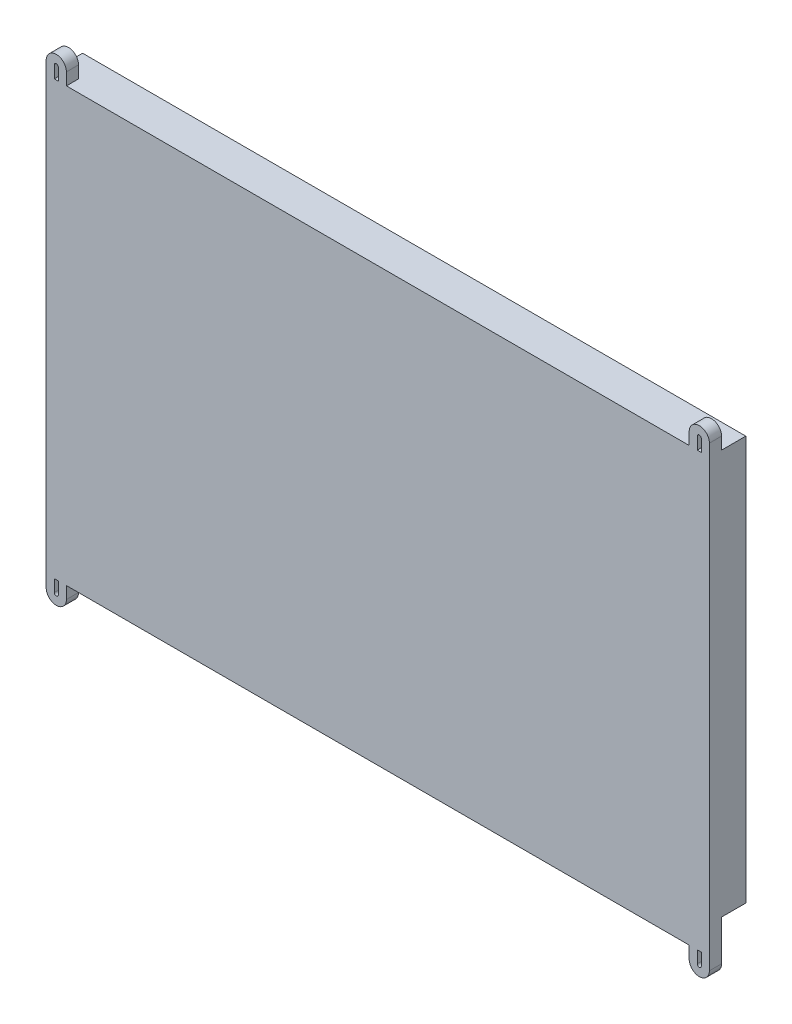
SolidWorks part; units mm, degrees
ref_plane "Plano frontal" through (0, 0, 0) normal (0, 0, 1) x (1, 0, 0)
ref_plane "Plano superior" through (0, 0, 0) normal (0, 1, 0) x (1, 0, 0)
ref_plane "Plano direito" through (0, 0, 0) normal (1, 0, 0) x (0, 0, -1)
sketch "Esboço1" plane through (0, 0, 0) normal (0, 0, 1) x (1, 0, 0)
  line L1 (-89.6416, -52.0983) -> (74.3584, -52.0983)
  line L2 (-89.6416, -52.0983) -> (-89.6416, 54.9017)
  line L3 (-89.6416, 54.9017) -> (74.3584, 54.9017)
  line L4 (74.3584, -52.0983) -> (74.3584, 54.9017)
  dimension "D1" = 107
  dimension "D2" = 164
extrude "Ressalto-extrusão1" add sketch "Esboço1" along normal mid plane 9
sketch "Esboço2" plane through (0, 0, 4.5) normal (0, 0, 1) x (1, 0, 0)
  line L0 (-89.6416, 54.9017) -> (-89.6416, 57.9017)
  line L1 (74.3584, 54.9017) -> (-89.6416, 54.9017) construction
  line L2 (-84.6416, 54.9017) -> (-84.6416, 57.9017)
  line L3 (69.3584, 54.9017) -> (69.3584, 57.9017)
  line L4 (74.3584, 54.9017) -> (74.3584, 57.9017)
  line L5 (-89.6416, 1.4017) -> (74.3584, 1.4017) construction
  line L9 (-89.6416, 54.9017) -> (-89.6416, -52.0983) construction
  line L10 (74.3584, -52.0983) -> (74.3584, 54.9017) construction
  line L11 (-84.6416, -52.0983) -> (-84.6416, -55.0983)
  line L12 (-89.6416, -52.0983) -> (-89.6416, -55.0983)
  line L13 (74.3584, -52.0983) -> (74.3584, -55.0983)
  line L14 (69.3584, -52.0983) -> (69.3584, -55.0983)
  arc A0 (-89.6416, 57.9017) -> (-84.6416, 57.9017) centre (-87.1416, 57.9017) cw
  arc A1 (69.3584, 57.9017) -> (74.3584, 57.9017) centre (71.8584, 57.9017) cw
  arc A2 (-89.6416, -55.0983) -> (-84.6416, -55.0983) centre (-87.1416, -55.0983) ccw
  arc A3 (69.3584, -55.0983) -> (74.3584, -55.0983) centre (71.8584, -55.0983) ccw
  point P17 (-89.6416, 1.4017)
  dimension "D1" = 5
  dimension "D2" = 0
  dimension "D3" = 3
extrude "Extrusão-Fina2" add sketch "Esboço2" against normal blind 3 thin
sketch "Esboço3" plane through (0, 0, -4.5) normal (0, 0, -1) x (-1, 0, 0)
  line L0 (-74.3584, -45.0983) -> (89.6416, -45.0983) construction
  line L1 (-74.3584, -52.0983) -> (-74.3584, 54.9017) construction
  line L2 (89.6416, 54.9017) -> (89.6416, -52.0983) construction
  line L4 (-74.3584, -45.0983) -> (89.6416, -45.0983)
  line L5 (-74.3584, -45.0983) -> (-74.3584, -52.0983)
  line L6 (-74.3584, -52.0983) -> (89.6416, -52.0983)
  line L7 (89.6416, -45.0983) -> (89.6416, -52.0983)
  dimension "D1" = 7
extrude "Corte-extrusão1" cut sketch "Esboço3" against normal blind 6
sketch "Esboço5" plane through (0, 0, -4.5) normal (0, 0, -1) x (-1, 0, 0)
  line L0 (-74.3584, 54.9017) -> (89.6416, 54.9017) construction
  line L1 (-70.3584, 51.9017) -> (83.4321, 51.9017)
  line L2 (-70.3584, 51.9017) -> (-70.3584, -37.3244)
  line L3 (-70.3584, -37.3244) -> (83.4321, -37.3244)
  line L4 (83.4321, 51.9017) -> (83.4321, -37.3244)
  line L6 (-74.3584, -45.0983) -> (-74.3584, 54.9017) construction
  dimension "D1" = 177.8
  dimension "D2" = 3
  dimension "D3" = 4
extrude "Corte-extrusão2" cut sketch "Esboço5" against normal blind 1
